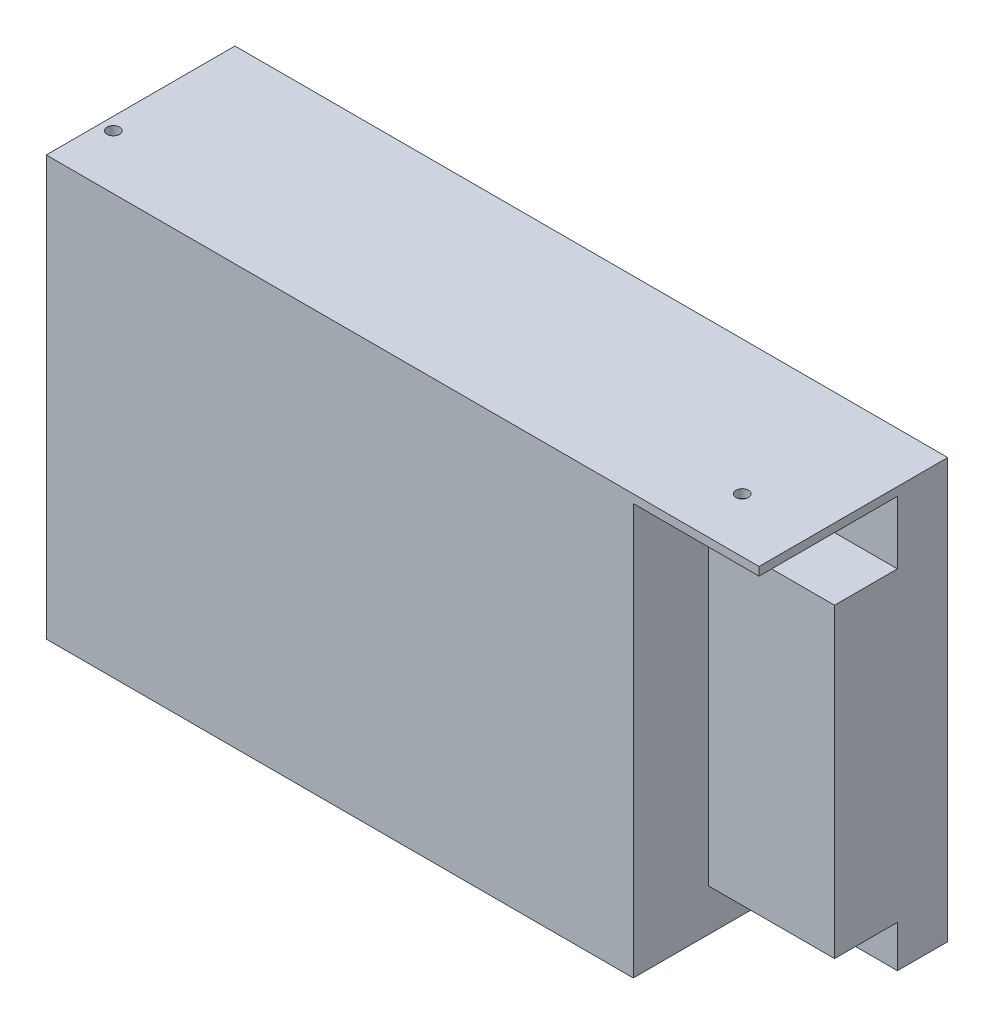
SolidWorks part; units mm, degrees
ref_plane "Front Plane" through (0, 0, 0) normal (0, 0, 1) x (1, 0, 0)
ref_plane "Top Plane" through (0, 0, 0) normal (0, 1, 0) x (1, 0, 0)
ref_plane "Right Plane" through (0, 0, 0) normal (1, 0, 0) x (0, 0, -1)
sketch "Sketch1" plane through (0, 0, 0) normal (0, 0, 1) x (1, 0, 0)
  line L1 (-8.8007, 4.7011) -> (161.1993, 4.7011)
  line L2 (-8.8007, 4.7011) -> (-8.8007, -95.2989)
  line L3 (-8.8007, -95.2989) -> (161.1993, -95.2989)
  line L4 (161.1993, 4.7011) -> (161.1993, -95.2989)
  dimension "D1" = 170
  dimension "D2" = 100
extrude "Boss-Extrude1" add sketch "Sketch1" along normal blind 45
sketch "Sketch3" plane through (0, 0, 45) normal (0, 0, 1) x (1, 0, 0)
  line L0 (-8.8007, 4.7011) -> (-8.8007, -95.2989) construction
  line L1 (161.1993, -95.2989) -> (131.1993, -95.2989)
  line L2 (161.1993, -95.2989) -> (161.1993, 2.7011)
  line L3 (161.1993, 2.7011) -> (131.1993, 2.7011)
  line L4 (131.1993, -95.2989) -> (131.1993, 2.7011)
  line L5 (161.1993, 4.7011) -> (-8.8007, 4.7011) construction
  dimension "D1" = 140
  dimension "D2" = 2
extrude "Cut-Extrude2" cut sketch "Sketch3" against normal blind 18
sketch "Sketch4" plane through (0, 0, 27) normal (0, 0, 1) x (1, 0, 0)
  line L0 (131.1993, 2.7011) -> (131.1993, -95.2989) construction
  line L1 (161.1993, -95.2989) -> (131.1993, -95.2989)
  line L2 (161.1993, -95.2989) -> (161.1993, -85.2989)
  line L3 (161.1993, -85.2989) -> (131.1993, -85.2989)
  line L4 (131.1993, -95.2989) -> (131.1993, -85.2989)
  line L5 (161.1993, -95.2989) -> (161.1993, 2.7011) construction
  line L6 (131.1993, 2.7011) -> (161.1993, 2.7011)
  line L7 (131.1993, 2.7011) -> (131.1993, -12.2989)
  line L8 (131.1993, -12.2989) -> (161.1993, -12.2989)
  line L9 (161.1993, 2.7011) -> (161.1993, -12.2989)
  dimension "D1" = 10
  dimension "D2" = 15
extrude "Cut-Extrude3" cut sketch "Sketch4" against normal blind 15
sketch "Sketch5" plane through (0, 4.7011, 0) normal (0, 1, 0) x (1, 0, 0)
  line L0 (156.1993, -45) -> (156.1993, -32) construction
  line L1 (161.1993, -45) -> (-8.8007, -45) construction
  line L2 (156.1993, -32) -> (161.1993, -32) construction
  line L3 (161.1993, -45) -> (161.1993, 0) construction
  line L4 (156.1993, -32) -> (-8.8007, -32) construction
  line L5 (-8.8007, -45) -> (-8.8007, 0) construction
  circle A0 centre (-5.8007, -32) radius 1.5
  circle A1 centre (144.1993, -32) radius 1.5
  dimension "D2" = 3
  dimension "D4" = 3
  dimension "D1" = 13
  dimension "D3" = 3
  dimension "D5" = 150
extrude "Cut-Extrude4" cut sketch "Sketch5" against normal blind 3
